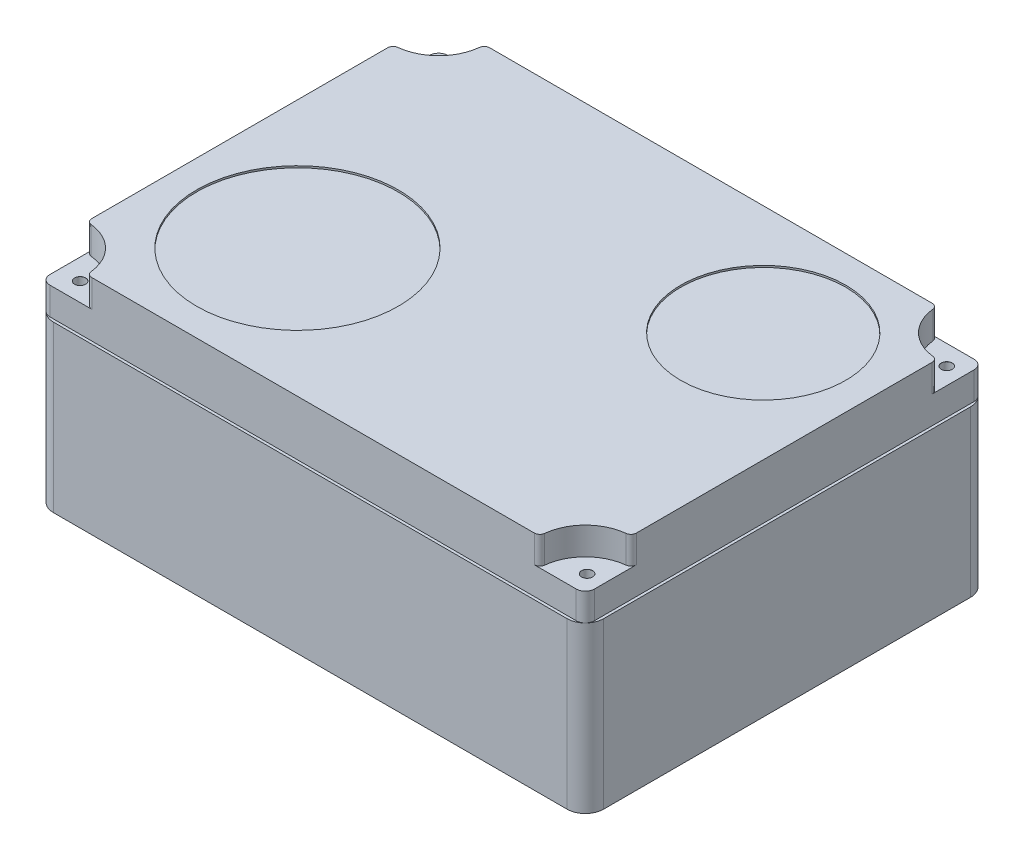
SolidWorks part; units mm, degrees
material "ABS"
ref_plane "Front Plane" through (0, 0, 0) normal (0, 0, 1) x (1, 0, 0)
ref_plane "Top Plane" through (0, 0, 0) normal (0, 1, 0) x (1, 0, 0)
ref_plane "Right Plane" through (0, 0, 0) normal (1, 0, 0) x (0, 0, -1)
sketch "Sketch1" plane through (0, 0, 0) normal (0, 1, 0) x (1, 0, 0)
  line L1 (150, -110) -> (-150, -110)
  line L2 (150, -110) -> (150, 110)
  line L3 (150, 110) -> (-150, 110)
  line L4 (-150, -110) -> (-150, 110)
  line L5 (150, -110) -> (-150, 110) construction
  line L6 (150, 110) -> (-150, -110) construction
  point P0 (0, 0)
  dimension "D1" = 300
  dimension "D2" = 220
extrude "Boss-Extrude1" add sketch "Sketch1" along normal blind 120
sketch "Sketch3" plane through (0, 120, 0) normal (0, 1, 0) x (1, 0, 0)
  line L8 (-148.5, 108.5) -> (-148.5, -108.5)
  line L9 (-148.5, -108.5) -> (148.5, -108.5)
  line L10 (148.5, -108.5) -> (148.5, 108.5)
  line L11 (148.5, 108.5) -> (-148.5, 108.5)
  line L12 (-148.5, 108.5) -> (-148.5, -108.5)
  line L13 (-148.5, -108.5) -> (148.5, -108.5)
  line L14 (148.5, -108.5) -> (148.5, 108.5)
  line L15 (148.5, 108.5) -> (-148.5, 108.5)
  dimension "D1" = 1.5
extrude "Cut-Extrude3" cut sketch "Sketch3" against normal blind 30 flip side to cut
sketch "Sketch4" plane through (0, 120, 0) normal (0, 1, 0) x (1, 0, 0)
  circle A0 centre (-148.5, -108.5) radius 25
  circle A1 centre (-148.5, 108.5) radius 25
  circle A2 centre (148.5, 108.5) radius 25
  circle A3 centre (148.5, -108.5) radius 25
  dimension "D1" = 50
extrude "Cut-Extrude4" cut sketch "Sketch4" against normal blind 15
fillet "Fillet1" radius 3 8 edges at (-148.5, 112.5, -83.5) (-123.5, 112.5, -108.5) (123.5, 112.5, -108.5) (148.5, 112.5, -83.5) (148.5, 112.5, 83.5) (123.5, 112.5, 108.5) (-123.5, 112.5, 108.5) (-148.5, 112.5, 83.5)
fillet "Fillet2" radius 5 4 edges at (148.5, 97.5, 108.5) (-148.5, 97.5, 108.5) (-148.5, 97.5, -108.5) (148.5, 97.5, -108.5)
fillet "Fillet3" radius 10 4 edges at (150, 45, -110) (150, 45, 110) (-150, 45, 110) (-150, 45, -110)
sketch "Sketch7" plane through (0, 105, 0) normal (0, 1, 0) x (1, 0, 0)
  point P0 (-137.1519, 97.744)
  point P2 (-137.1519, -98.3646)
  point P4 (139.324, -98.3646)
  point P6 (139.324, 97.744)
hole_wizard "Ø6.0mm Dowel Hole1" positions "Sketch7" profile "Sketch8" hole size "Ø6.0" standard "ANSI Metric"
sketch "Sketch8" plane through (-137.1519, 105, -97.744) normal (1, 0, 0) x (0, 0, 1)
  line L0 (0, 0) -> (0, 31.8026)
  line L1 (0, 31.8026) -> (3, 30)
  line L2 (3, 30) -> (3, 0.025)
  line L3 (3, 0.025) -> (3.025, 0)
  line L5 (3.025, 0) -> (0, 0)
  line L6 (-3, 0.025) -> (-3.025, 0) construction
  line L10 (0, 31.8026) -> (-3, 30) construction
  line L11 (0, -6.35) -> (0, 107.95) construction
  dimension "Hole Dia." = 6
  dimension "Hole Depth" = 30
  dimension "Near C'Sink Dia." = 6.05
  dimension "Near C'Sink Angle" = 90
  dimension "Drill Angle" = 118
sketch "Sketch10" plane through (0, 120, 0) normal (0, 1, 0) x (1, 0, 0)
  line L0 (-120.6612, -108.5) -> (120.6612, -108.5) construction
  line L1 (-148.5, 103.5) -> (-148.5, -103.5) construction
  line L2 (148.5, -80.6612) -> (148.5, 80.6612) construction
  line L3 (120.6612, 108.5) -> (-120.6612, 108.5) construction
  circle A0 centre (-78.5, -38.5) radius 55
  circle A1 centre (88.5, 48.5) radius 45
  dimension "D1" = 110
  dimension "D2" = 90
  dimension "D3" = 70
  dimension "D4" = 70
  dimension "D5" = 60
  dimension "D6" = 60
extrude "Cut-Extrude5" cut sketch "Sketch10" against normal blind 1
sketch "Sketch11" plane through (0, 0, 0) normal (0, -1, 0) x (1, 0, 0)
  line L0 (150, 100) -> (150, -100) construction
  line L3 (-150, -100) -> (-150, 100) construction
  line L4 (140, -110) -> (-140, -110) construction
  line L5 (-140, 110) -> (140, 110) construction
  circle A0 centre (120, 0) radius 9
  circle A1 centre (60, 0) radius 9
  circle A2 centre (-125, -75) radius 9
  dimension "D1" = 18
  dimension "D2" = 30
  dimension "D3" = 90
  dimension "D4" = 25
  dimension "D5" = 35
  dimension "D6" = 110
  dimension "D7" = 110
extrude "Cut-Extrude6" cut sketch "Sketch11" against normal blind 30
